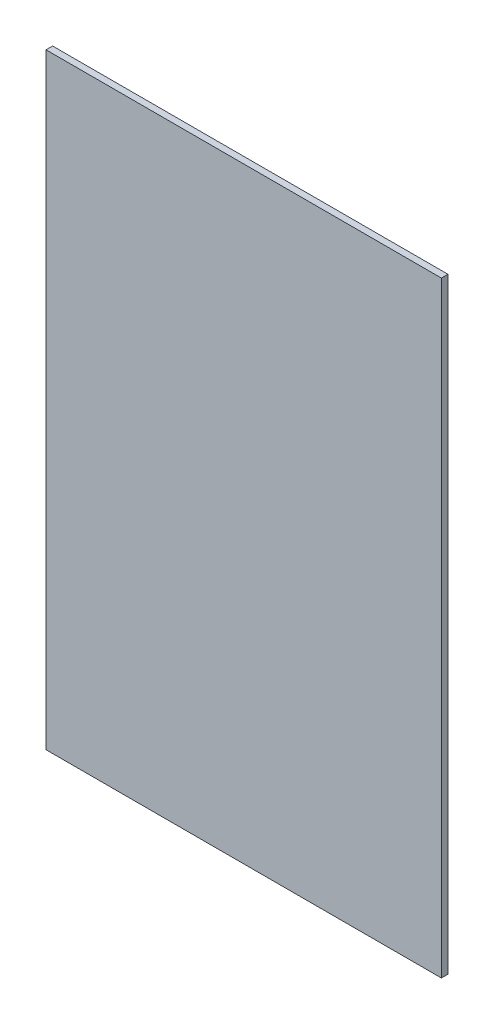
SolidWorks part; units mm, degrees
ref_plane "Alzado" through (0, 0, 0) normal (0, 0, 1) x (1, 0, 0)
ref_plane "Planta" through (0, 0, 0) normal (0, 1, 0) x (1, 0, 0)
ref_plane "Vista lateral" through (0, 0, 0) normal (1, 0, 0) x (0, 0, -1)
sketch "Croquis1" plane through (0, 0, 0) normal (0, 0, 1) x (1, 0, 0)
  line L1 (-300, 460) -> (300, 460)
  line L2 (-300, 460) -> (-300, -460)
  line L3 (-300, -460) -> (300, -460)
  line L4 (300, 460) -> (300, -460)
  line L5 (-300, 460) -> (300, -460) construction
  line L6 (-300, -460) -> (300, 460) construction
  point P0 (0, 0)
  dimension "D1" = 600
  dimension "D2" = 920
extrude "Saliente-Extruir1" add sketch "Croquis1" along normal blind 10
